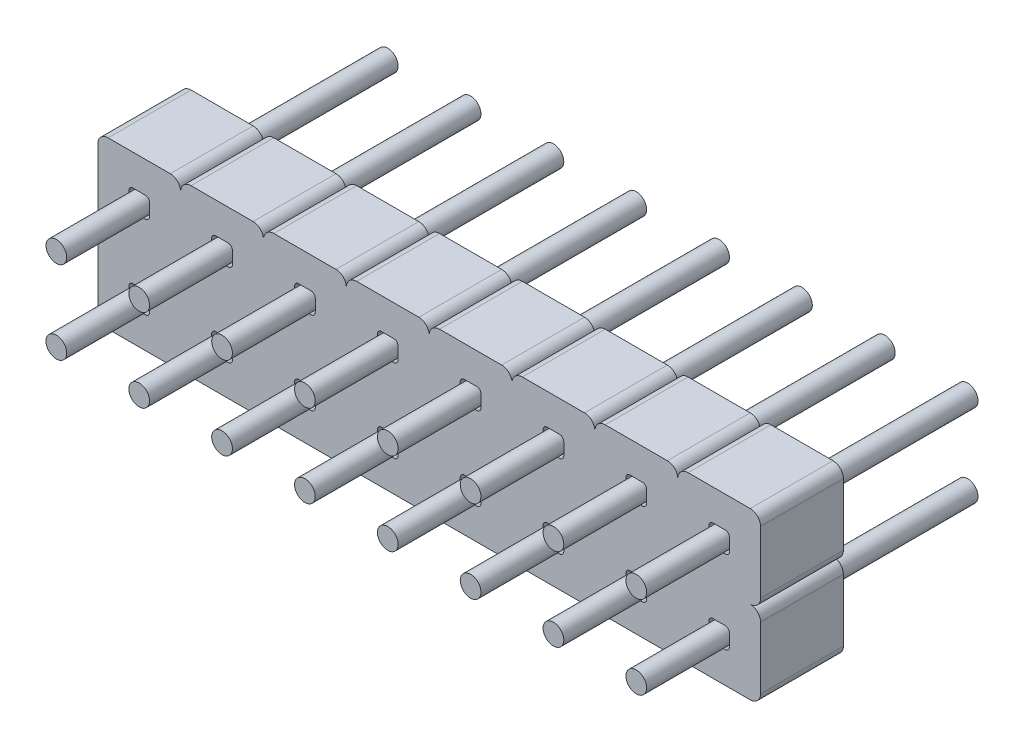
SolidWorks part; units mm, degrees
ref_plane "前视基准面" through (0, 0, 0) normal (0, 0, 1) x (1, 0, 0)
ref_plane "上视基准面" through (0, 0, 0) normal (0, 1, 0) x (1, 0, 0)
ref_plane "右视基准面" through (0, 0, 0) normal (1, 0, 0) x (0, 0, -1)
sketch "草图1" plane through (0, 0, 0) normal (0, 0, 1) x (1, 0, 0)
  line L0 (1, 0) -> (1, -2) construction
  line L1 (0.25, 0) -> (1.75, 0)
  line L2 (0, -0.25) -> (0, -1.75)
  line L3 (0.25, -2) -> (1.75, -2)
  line L4 (2, -0.25) -> (2, -1.75)
  line L5 (0, -1) -> (2, -1) construction
  line L7 (0.85, -0.75) -> (1.15, -0.75)
  line L8 (0.75, -0.85) -> (0.75, -1.15)
  line L9 (0.85, -1.25) -> (1.15, -1.25)
  line L10 (1.25, -0.85) -> (1.25, -1.15)
  arc A0 (2, -1.75) -> (1.75, -2) centre (1.75, -1.75) cw
  arc A1 (0.25, -2) -> (0, -1.75) centre (0.25, -1.75) cw
  arc A2 (0.25, 0) -> (0, -0.25) centre (0.25, -0.25) ccw
  arc A3 (2, -0.25) -> (1.75, 0) centre (1.75, -0.25) ccw
  circle A4 centre (1, -1) radius 0.25 construction
  arc A5 (0.75, -1.15) -> (0.85, -1.25) centre (0.85, -1.15) ccw
  arc A6 (1.15, -1.25) -> (1.25, -1.15) centre (1.15, -1.15) ccw
  arc A7 (1.25, -0.85) -> (1.15, -0.75) centre (1.15, -0.85) ccw
  arc A8 (0.85, -0.75) -> (0.75, -0.85) centre (0.85, -0.85) ccw
  point P11 (0, 0)
  dimension "D3" = 0.25
  dimension "D4" = 0.5
  dimension "D5" = 0.1
  dimension "D1" = 2
  dimension "D2" = 2
extrude "凸台-拉伸1" add sketch "草图1" along normal blind 2
pattern_linear "阵列(线性)2" count 8 spacing 2 along (1, 0, 0) count 2 spacing 2 along (0, -1, 0) of "凸台-拉伸1"
sketch "草图3" plane through (0, 0, 0) normal (0, 0, -1) x (-1, 0, 0)
  line L0 (-1, 0) -> (-1, -4) construction
  line L1 (-1.75, 0) -> (-0.25, 0) construction
  line L2 (-0.25, -4) -> (-1.75, -4) construction
  line L3 (0, -1) -> (-2.4529, -1) construction
  line L4 (0, -0.25) -> (0, -1.75) construction
  line L5 (-0.25, -2) -> (-1.75, -2) construction
  line L9 (-0.75, -0.85) -> (-0.75, -1.15) construction
  line L10 (-0.85, -1.25) -> (-1.15, -1.25) construction
  line L11 (-1.25, -0.85) -> (-1.25, -1.15) construction
  line L12 (-0.85, -0.75) -> (-1.15, -0.75) construction
  circle A0 centre (-1, -1) radius 0.25
  arc A4 (-1.25, -1.15) -> (-1.15, -1.25) centre (-1.15, -1.15) ccw construction
  arc A5 (-0.75, -1.15) -> (-0.85, -1.25) centre (-0.85, -1.15) cw construction
  arc A6 (-0.85, -0.75) -> (-0.75, -0.85) centre (-0.85, -0.85) cw construction
  arc A7 (-1.15, -0.75) -> (-1.25, -0.85) centre (-1.15, -0.85) ccw construction
  point P26 (-1, -1.25)
  point P28 (-0.75, -1)
  point P29 (-1.25, -1)
  point P31 (-1.25, -1.25)
  point P34 (-0.75, -1.25)
  point P37 (-0.75, -0.75)
  point P40 (-1.25, -0.75)
  dimension "D4" = 0.1
  dimension "D2" = 0.25
  dimension "D3" = 0.25
ref_plane "基准面1" through (1, 0, 0) normal (-1, 0, 0) x (0, 0, 1)
ref_plane "基准面2" through (0, -2, 0) normal (0, -1, 0) x (1, 0, 0)
extrude "凸台-拉伸2" add sketch "草图3" along normal mid plane 8 separate body
pattern_linear "阵列(线性)3" count 8 spacing 2 along (1, 0, 0) count 2 spacing 2 along (0, -1, 0) of "凸台-拉伸2"
